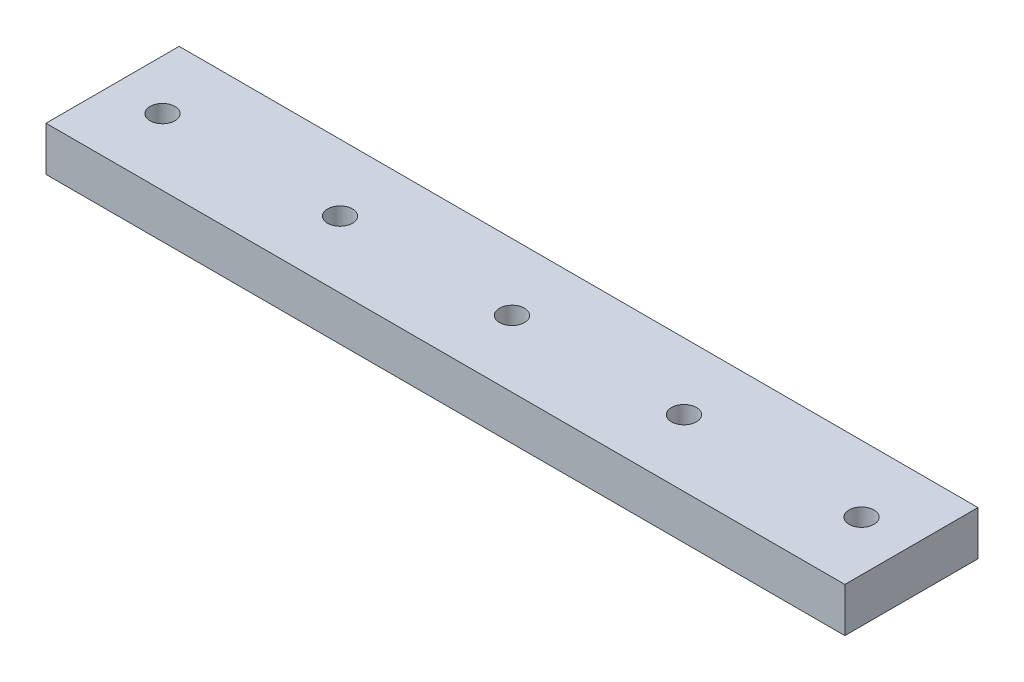
SolidWorks part; units mm, degrees
material "6061-T4 (SS)"
ref_plane "Front Plane" through (0, 0, 0) normal (0, 0, 1) x (1, 0, 0)
ref_plane "Top Plane" through (0, 0, 0) normal (0, 1, 0) x (1, 0, 0)
ref_plane "Right Plane" through (0, 0, 0) normal (1, 0, 0) x (0, 0, -1)
sketch "Sketch1" plane through (0, 0, 0) normal (0, 1, 0) x (1, 0, 0)
  line L0 (0, -19.05) -> (228.6, -19.05) construction
  line L1 (0, 0) -> (228.6, 0)
  line L2 (0, 0) -> (0, -38.1)
  line L3 (0, -38.1) -> (228.6, -38.1)
  line L4 (228.6, 0) -> (228.6, -38.1)
  circle A0 centre (14.2875, -19.05) radius 3.5719
  circle A1 centre (65.0875, -19.05) radius 3.5719
  circle A2 centre (114.3, -19.05) radius 3.5719
  circle A3 centre (163.5125, -19.05) radius 3.5719
  circle A4 centre (214.3125, -19.05) radius 3.5719
  dimension "D3" = 7.1437
  dimension "D1" = 38.1
  dimension "D2" = 228.6
  dimension "D4" = 14.2875
  dimension "D5" = 65.0875
  dimension "D6" = 114.3
  dimension "D7" = 163.5125
  dimension "D8" = 214.3125
extrude "Boss-Extrude1" add sketch "Sketch1" along normal blind 12.7
